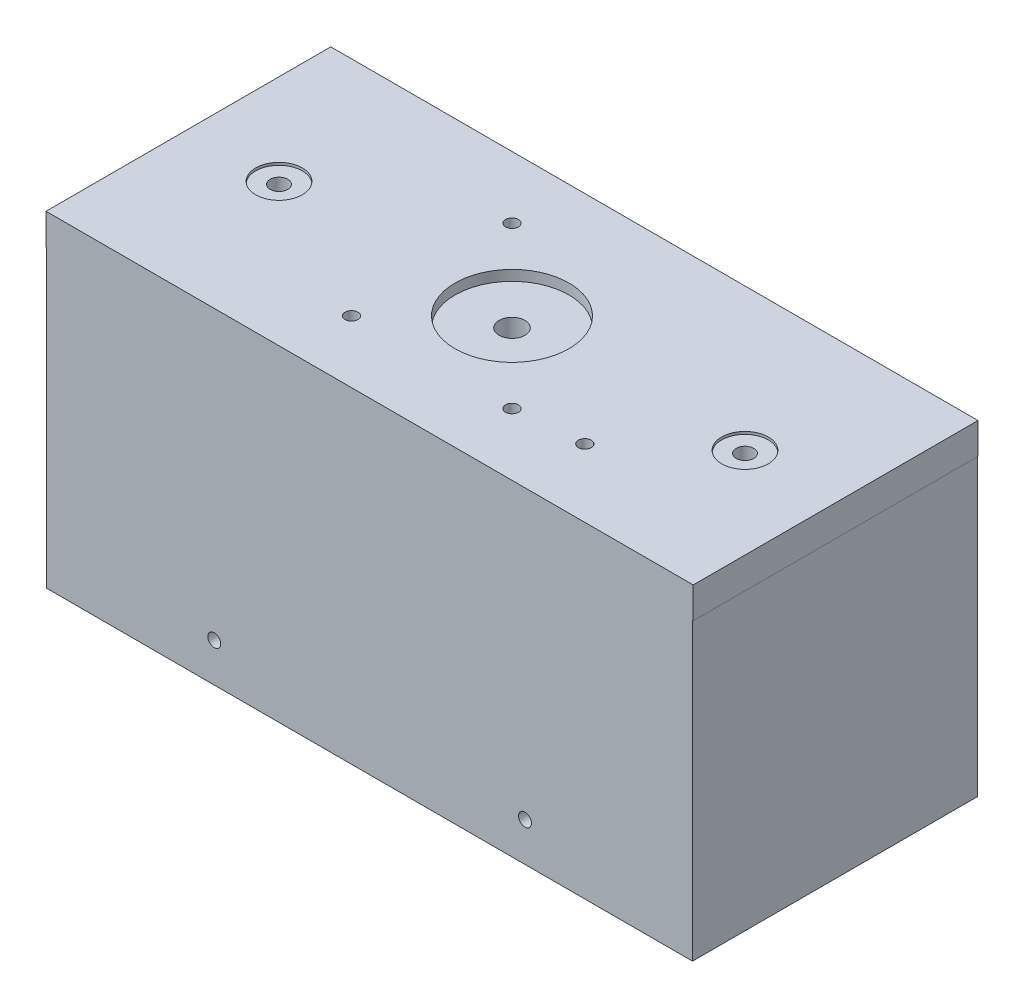
SolidWorks part; units mm, degrees
ref_plane "前视基准面" through (0, 0, 0) normal (0, 0, 1) x (1, 0, 0)
ref_plane "上视基准面" through (0, 0, 0) normal (0, 1, 0) x (1, 0, 0)
ref_plane "右视基准面" through (0, 0, 0) normal (1, 0, 0) x (0, 0, -1)
sketch "草图1" plane through (0, 0, 0) normal (0, 1, 0) x (1, 0, 0)
  line L1 (-62.5, 27.5) -> (62.5, 27.5)
  line L2 (-62.5, 27.5) -> (-62.5, -27.5)
  line L3 (-62.5, -27.5) -> (62.5, -27.5)
  line L4 (62.5, 27.5) -> (62.5, -27.5)
  line L5 (-62.5, 27.5) -> (62.5, -27.5) construction
  line L6 (-62.5, -27.5) -> (62.5, 27.5) construction
  point P0 (0, 0)
  dimension "D1" = 125
  dimension "D2" = 55
extrude "凸台-拉伸1" add sketch "草图1" along normal blind 6
sketch "草图2" plane through (0, 6, 0) normal (0, 1, 0) x (1, 0, 0)
  circle A0 centre (0, 0) radius 11
  dimension "D1" = 22
extrude "切除-拉伸1" cut sketch "草图2" against normal blind 2
sketch "草图3" plane through (0, 4, 0) normal (0, 1, 0) x (1, 0, 0)
  circle A0 centre (0, 0) radius 2.5
  dimension "D1" = 5
extrude "切除-拉伸2" cut sketch "草图3" against normal up to next
hole_wizard "M3 螺纹孔1" positions "草图4" profile "草图5" tap size "M3" standard "GB"
sketch "草图4" plane through (0, 6, 0) normal (0, 1, 0) x (1, 0, 0)
  point P0 (28.4443, -14.3795)
  point P3 (15.5, -15.5)
  point P6 (-15.5, -15.5)
  point P9 (-15.5, 15.5)
sketch "草图5" plane through (28.4443, 6, 14.3795) normal (1, 0, 0) x (0, 0, 1)
  line L0 (0, 0) -> (0, 8.2511)
  line L1 (0, 8.2511) -> (1.25, 7.5)
  line L2 (1.25, 7.5) -> (1.25, 0)
  line L5 (1.25, 0) -> (0, 0)
  line L10 (0, 8.2511) -> (-1.25, 7.5) construction
  line L11 (0, -6.35) -> (0, 107.95) construction
  dimension "螺纹孔钻头直径" = 2.5
  dimension "螺纹孔钻头深度" = 7.5
  dimension "导头角度" = 118
cosmetic thread "孔螺蚊线11" parameters "D1"=6, "D2"=3.5
cosmetic thread "孔螺蚊线14" parameters "D1"=6, "D2"=3.5
cosmetic thread "孔螺蚊线15" parameters "D1"=6, "D2"=3.5
cosmetic thread "孔螺蚊线16" parameters "D1"=6, "D2"=3.5
sketch "草图6" plane through (0, 0, 0) normal (0, -1, 0) x (1, 0, 0)
  line L0 (-62.5, 27.5) -> (62.5, 27.5) construction
  line L1 (60, -25) -> (-60, -25)
  line L2 (60, -25) -> (60, 25)
  line L3 (60, 25) -> (-60, 25)
  line L4 (-60, -25) -> (-60, 25)
  line L5 (60, -25) -> (-60, 25) construction
  line L6 (60, 25) -> (-60, -25) construction
  line L7 (62.362, -27.5) -> (-62.362, -27.5)
  line L8 (62.362, -27.5) -> (62.362, 27.5)
  line L9 (62.362, 27.5) -> (-62.362, 27.5)
  line L10 (-62.362, -27.5) -> (-62.362, 27.5)
  line L11 (62.362, -27.5) -> (-62.362, 27.5) construction
  line L12 (62.362, 27.5) -> (-62.362, -27.5) construction
  point P0 (0, 0)
  point P7 (0, 0)
extrude "凸台-拉伸2" add sketch "草图6" along normal up to vertex (57 mm away)
sketch "草图7" plane through (0, 0, -27.5) normal (0, 0, -1) x (-1, 0, 0)
  line L4 (-62.5, 6) -> (-62.5, 0)
  line L5 (-62.5, 0) -> (-62.362, 0)
  line L6 (62.5, 0) -> (62.5, 6)
  line L7 (62.5, 6) -> (-62.5, 6)
  line L8 (-62.5, 6) -> (-62.5, 0)
  line L10 (62.5, 0) -> (62.5, 6)
  line L11 (62.5, 6) -> (-62.5, 6)
  line L16 (-62.5, 0) -> (-62.362, 0)
  line L38 (-62.362, -57) -> (62.362, -57)
  line L40 (-62.362, -57) -> (62.362, -57)
  line L42 (-62.362, 0) -> (-62.362, -57)
  line L44 (-62.362, 0) -> (-62.362, -57)
  line L45 (62.362, -57) -> (62.362, 0)
  line L46 (62.362, -57) -> (62.362, 0)
  line L47 (62.362, 0) -> (62.5, 0)
  line L48 (62.362, 0) -> (62.5, 0)
  circle A0 centre (30, -49.5) radius 1.25 construction
  circle A1 centre (-30, -49.5) radius 1.25 construction
  circle A2 centre (30, -49.5) radius 1.25
  circle A3 centre (-30, -49.5) radius 1.25
  dimension "D1" = 0
hole_wizard "M3 螺纹孔2" positions "草图8" profile "草图9" tap size "M3" standard "GB"
sketch "草图8" plane through (0, 0, -27.5) normal (0, 0, -1) x (-1, 0, 0)
  point P0 (30, -49.5)
  point P3 (-30, -49.5)
sketch "草图9" plane through (-30, -49.5, -27.5) normal (1, 0, 0) x (0, 1, 0)
  line L0 (0, 0) -> (0, 2.5)
  line L1 (0, 2.5) -> (1.25, 2.5)
  line L2 (1.25, 2.5) -> (1.25, 0)
  line L5 (1.25, 0) -> (0, 0)
  line L11 (0, -6.35) -> (0, 107.95) construction
  dimension "通孔螺纹孔钻头直径" = 2.5
  dimension "通孔螺纹孔钻头深度" = 2.5
cosmetic thread "孔螺蚊线5" parameters "D2"=3
cosmetic thread "孔螺蚊线6" parameters "D2"=3
hole_wizard "M3 螺纹孔3" positions "草图11" profile "草图12" tap size "M3" standard "GB" end condition up to next
sketch "草图11" plane through (0, 0, 27.5) normal (0, 0, 1) x (1, 0, 0)
  point P0 (30, -49.5)
  point P3 (-30, -49.5)
sketch "草图12" plane through (30, -49.5, 27.5) normal (1, 0, 0) x (0, -1, 0)
  line L0 (0, 0) -> (0, 2.5)
  line L1 (0, 2.5) -> (1.25, 2.5)
  line L2 (1.25, 2.5) -> (1.25, 0)
  line L5 (1.25, 0) -> (0, 0)
  line L11 (0, -6.35) -> (0, 107.95) construction
  dimension "通孔螺纹孔钻头直径" = 2.5
  dimension "通孔螺纹孔钻头深度" = 2.5
cosmetic thread "孔螺蚊线7" parameters "D2"=3
cosmetic thread "孔螺蚊线17" parameters "D2"=3
sketch "草图13" plane through (0, 6, 0) normal (0, 1, 0) x (1, 0, 0)
  line L0 (0, 0) -> (45, 0) construction
  line L1 (0, 0) -> (-45, 0) construction
  circle A0 centre (-45, 0) radius 7.9824 construction
  circle A1 centre (45, 0) radius 7.9824 construction
  dimension "D1" = 90
  dimension "D2" = 45
hole_wizard "M3 六角头螺栓的柱形沉头孔1" positions "3D草图1" profile "草图14" counterbore size "M3" standard "GB"
sketch3d "3D草图1"
  point P0 (-45, 6, 0)
  point P3 (45, 6, 0)
sketch "草图14" plane through (-45, 6, 0) normal (1, 0, 0) x (0, 0, 1)
  line L0 (0, 0) -> (0, 6.0215)
  line L1 (0, 6.0215) -> (1.7, 5)
  line L2 (1.7, 5) -> (1.7, 0.5)
  line L3 (1.7, 0.5) -> (4.5, 0.5)
  line L4 (4.5, 0.5) -> (4.5, 0)
  line L5 (4.5, 0) -> (0, 0)
  line L10 (0, 6.0215) -> (-1.7, 5) construction
  line L11 (0, -6.35) -> (0, 107.95) construction
  dimension "孔直径" = 3.4
  dimension "孔深度" = 5
  dimension "柱形沉头孔直径" = 9
  dimension "柱形沉头孔深度" = 0.5
  dimension "导头角度" = 118
